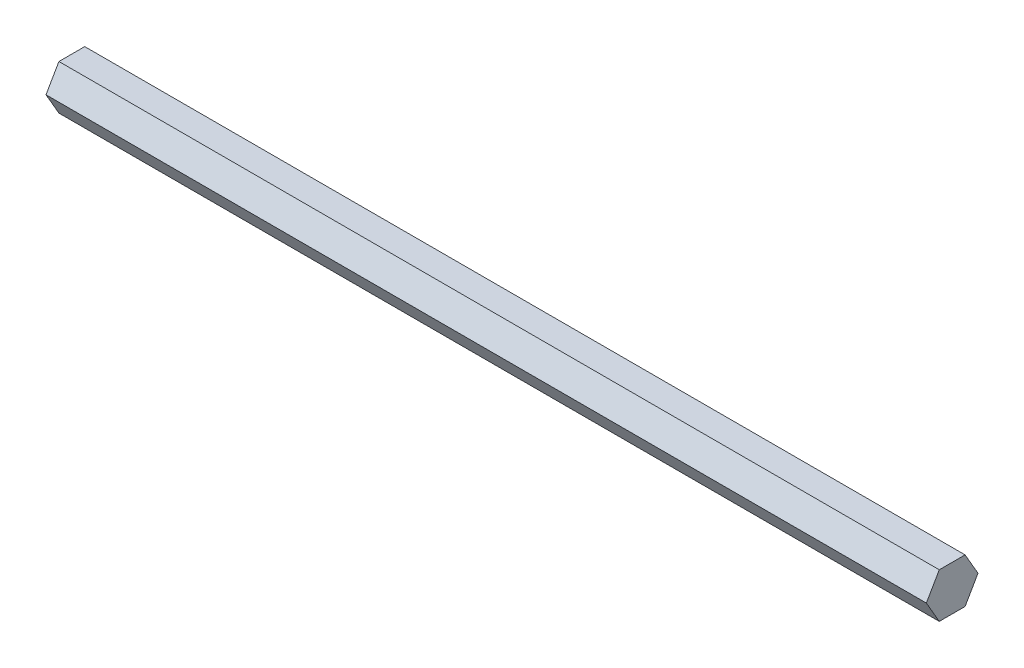
SolidWorks part; units mm, degrees
ref_plane "Alzado" through (0, 0, 0) normal (0, 0, 1) x (1, 0, 0)
ref_plane "Planta" through (0, 0, 0) normal (0, 1, 0) x (1, 0, 0)
ref_plane "Vista lateral" through (0, 0, 0) normal (1, 0, 0) x (0, 0, -1)
sketch "Croquis1" plane through (0, 0, 0) normal (1, 0, 0) x (0, 0, -1)
  line L1 (7.3323, 0) -> (3.6662, 6.35)
  line L2 (3.6662, 6.35) -> (-3.6662, 6.35)
  line L3 (-3.6662, 6.35) -> (-7.3323, 0)
  line L4 (-7.3323, 0) -> (-3.6662, -6.35)
  line L5 (-3.6662, -6.35) -> (3.6662, -6.35)
  line L6 (3.6662, -6.35) -> (7.3323, 0)
  circle A0 centre (0, 0) radius 6.35 construction
  dimension "D1" = 12.7
extrude "Saliente-Extruir1" add sketch "Croquis1" along normal blind 250
